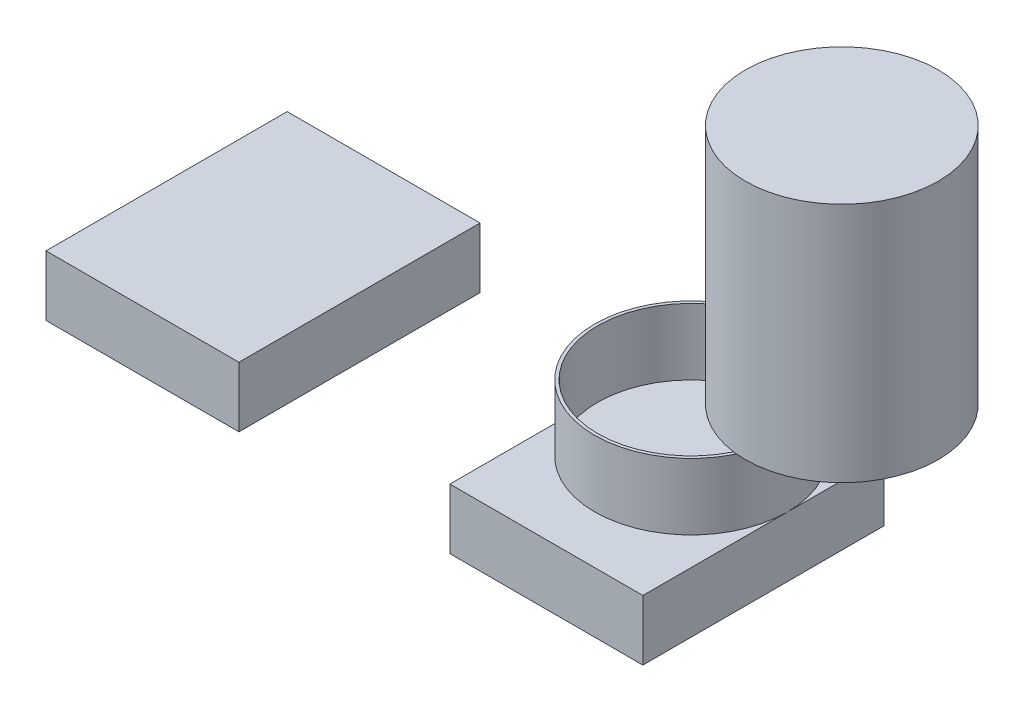
SolidWorks part; units mm, degrees
ref_plane "Front Plane" through (0, 0, 0) normal (0, 0, 1) x (1, 0, 0)
ref_plane "Top Plane" through (0, 0, 0) normal (0, 1, 0) x (1, 0, 0)
ref_plane "Right Plane" through (0, 0, 0) normal (1, 0, 0) x (0, 0, -1)
sketch "Sketch2" plane through (0, 0, 0) normal (0, 1, 0) x (1, 0, 0)
  line L0 (-830, -240) -> (-510, -240)
  line L1 (-160, -240) -> (160, -240)
  line L2 (-160, -240) -> (-160, 160)
  line L3 (-160, 160) -> (160, 160)
  line L4 (160, -240) -> (160, 160)
  line L5 (-160, -240) -> (160, 160) construction
  line L6 (-160, 160) -> (160, -240) construction
  line L7 (-830, -240) -> (-830, 160)
  line L8 (-830, 160) -> (-510, 160)
  line L9 (-510, -240) -> (-510, 160)
  line L10 (-830, -240) -> (-510, 160) construction
  line L11 (-830, 160) -> (-510, -240) construction
  point P0 (0, -40)
  point P6 (-670, -40)
  dimension "D1" = 320
  dimension "D2" = 400
  dimension "D3" = 40
  dimension "D4" = 320
  dimension "D5" = 400
  dimension "D6" = 670
extrude "Boss-Extrude1" add sketch "Sketch2" along normal blind 100
ref_plane "Plane1" through (0, 300, 0) normal (0, 1, 0) x (1, 0, 0)
sketch "Sketch4" plane through (0, 100, 0) normal (0, 1, 0) x (1, 0, 0)
  circle A0 centre (0, 0) radius 160
  circle A1 centre (0, 0) radius 155
  dimension "D1" = 310
extrude "Boss-Extrude3" add sketch "Sketch4" along normal blind 110
sketch "Sketch5" plane through (0, 300, 0) normal (0, 1, 0) x (1, 0, 0)
  circle A0 centre (250, 0) radius 160
  dimension "D2" = 320
  dimension "D1" = 250
extrude "Boss-Extrude4" add sketch "Sketch5" along normal blind 400 separate body
